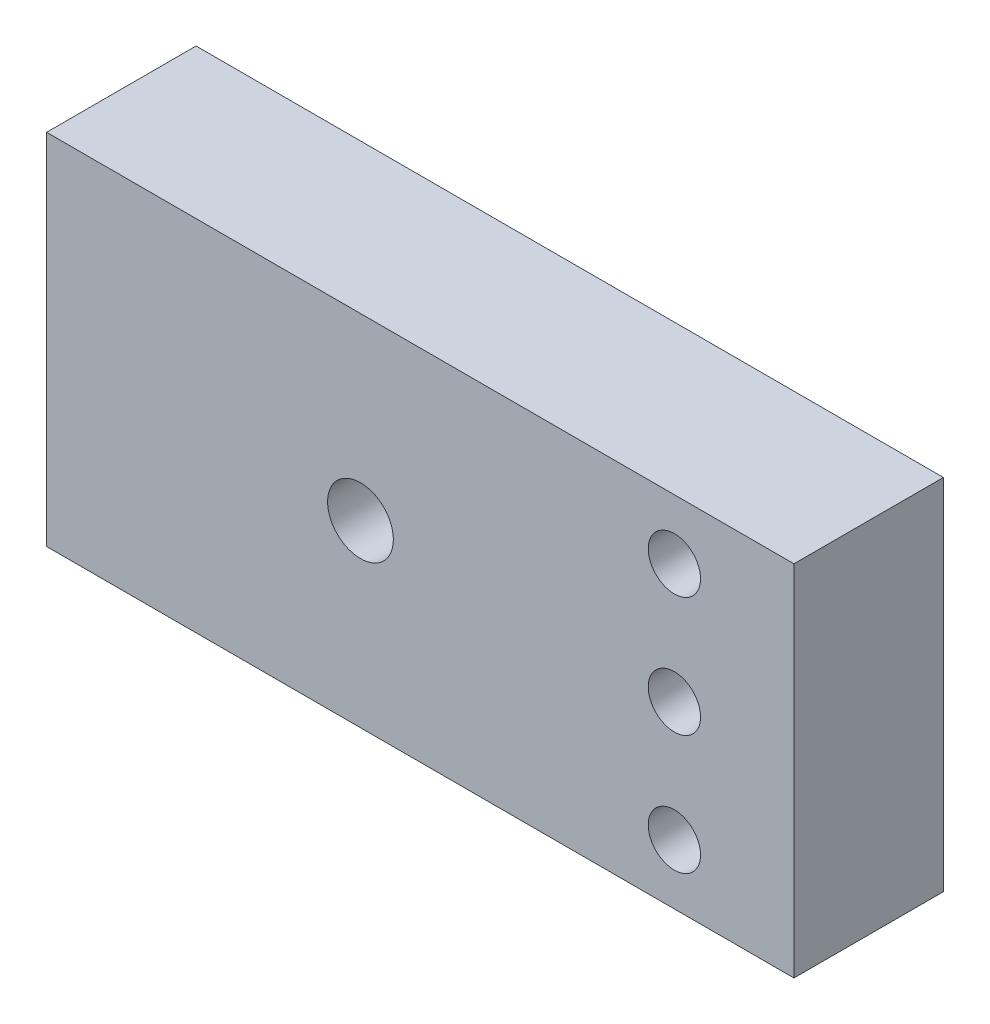
SolidWorks part; units mm, degrees
material "1.0553 (S355J0)"
ref_plane "XY Plane" through (0, 0, 0) normal (0, 0, 1) x (1, 0, 0)
ref_plane "XZ Plane" through (0, 0, 0) normal (0, 1, 0) x (1, 0, 0)
ref_plane "YZ Plane" through (0, 0, 0) normal (1, 0, 0) x (0, 0, -1)
sketch "Sketch1" plane through (0, 0, 0) normal (0, 0, 1) x (1, 0, 0)
  line L1 (-125, -60) -> (125, -60)
  line L2 (-125, -60) -> (-125, 60)
  line L3 (-125, 60) -> (125, 60)
  line L4 (125, -60) -> (125, 60)
  line L5 (-125, -60) -> (125, 60) construction
  line L6 (-125, 60) -> (125, -60) construction
  point P0 (0, 0)
  dimension "D1" = 250
  dimension "D2" = 120
extrude "Boss-Extrude1" add sketch "Sketch1" against normal blind 50
hole_wizard "Ø22.0 (22) Diameter Hole1" positions "Sketch3" profile "Sketch4" hole size "Ø22.0" standard "ISO" end condition through all
sketch "Sketch3" plane through (0, 0, 0) normal (0, 0, 1) x (1, 0, 0)
  line L0 (0, 0) -> (-20, 0) construction
  line L2 (125, -60) -> (125, 60) construction
  point P0 (-20, 0)
  dimension "D1" = 145
sketch "Sketch4" plane through (-20, 0, 0) normal (1, 0, 0) x (0, -1, 0)
  line L0 (0, 0) -> (0, 50)
  line L1 (0, 50) -> (11, 50)
  line L2 (11, 50) -> (11, 0)
  line L5 (11, 0) -> (0, 0)
  line L11 (0, -6.35) -> (0, 107.95) construction
  dimension "Thru Hole Dia." = 22
  dimension "Thru Hole Depth" = 50
hole_wizard "M20 Tapped Hole1" positions "Sketch5" profile "Sketch6" tap size "M20" standard "ISO" end condition through all
sketch "Sketch5" plane through (0, 0, 0) normal (0, 0, 1) x (1, 0, 0)
  line L0 (0, 0) -> (85, 0) construction
  line L2 (125, -60) -> (125, 60) construction
  point P0 (85, 0)
  dimension "D1" = 40
sketch "Sketch6" plane through (85, 0, 0) normal (1, 0, 0) x (0, -1, 0)
  line L0 (0, 0) -> (0, 50)
  line L1 (0, 50) -> (8.75, 50)
  line L2 (8.75, 50) -> (8.75, 0)
  line L5 (8.75, 0) -> (0, 0)
  line L11 (0, -6.35) -> (0, 107.95) construction
  dimension "Thru Tap Drill Dia." = 17.5
  dimension "Thru Tap Drill Depth" = 50
cosmetic thread "Hole Thread1" parameters "D2"=20
pattern_linear "LPattern1" count 2 spacing 40 along (0, -1, 0) count 2 spacing 40 along (0, 1, 0) of "M20 Tapped Hole1"
